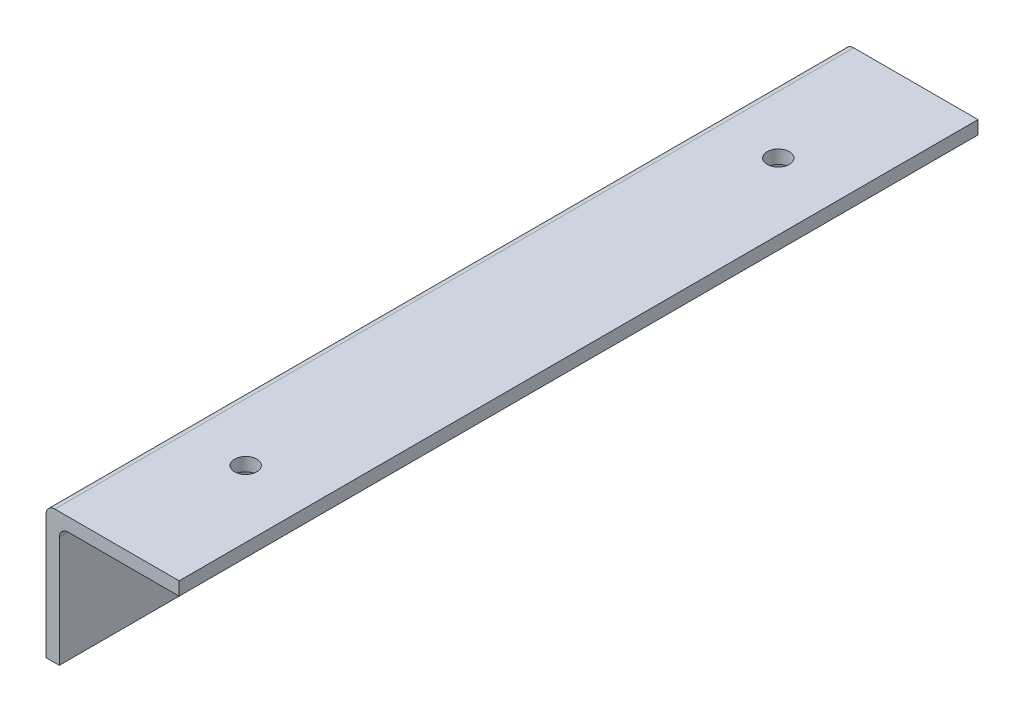
SolidWorks part; units mm, degrees
ref_plane "Plan de face" through (0, 0, 0) normal (0, 0, 1) x (1, 0, 0)
ref_plane "Plan de dessus" through (0, 0, 0) normal (0, 1, 0) x (1, 0, 0)
ref_plane "Plan de droite" through (0, 0, 0) normal (1, 0, 0) x (0, 0, -1)
sketch "Esquisse1" plane through (0, 0, 0) normal (0, 0, 1) x (1, 0, 0)
  line L0 (0, 0) -> (0, -30)
  line L1 (0, -30) -> (3, -30)
  line L2 (3, -30) -> (3, -3)
  line L3 (3, -3) -> (30, -3)
  line L4 (30, -3) -> (30, 0)
  line L5 (30, 0) -> (0, 0)
  dimension "D1" = 30
  dimension "D2" = 30
  dimension "D3" = 3
  dimension "D4" = 3
extrude "Boss.-Extru.1" add sketch "Esquisse1" along normal blind 180
sketch "Esquisse2" plane through (3, 0, 0) normal (1, 0, 0) x (0, 0, -1)
  line L0 (-180, -30) -> (0, -30) construction
  line L1 (-180, -30) -> (-180, -3) construction
  line L2 (0, -30) -> (0, -3) construction
  circle A0 centre (-30, -15) radius 3
  circle A1 centre (-150, -15) radius 3
  dimension "D1" = 6
  dimension "D2" = 6
  dimension "D3" = 15
  dimension "D4" = 15
  dimension "D5" = 30
  dimension "D6" = 30
  dimension "D7" = 120
extrude "Enlèv. mat.-Extru.1" cut sketch "Esquisse2" against normal blind 180
sketch "Esquisse3" plane through (0, -3, 0) normal (0, -1, 0) x (1, 0, 0)
  line L0 (3, 0) -> (30, 0) construction
  line L1 (3, 180) -> (30, 180) construction
  line L2 (30, 180) -> (0, 180) construction
  line L3 (0, 180) -> (0, 0) construction
  circle A0 centre (15, 150) radius 2.5
  circle A1 centre (15, 30) radius 2.5
  dimension "D1" = 5
  dimension "D2" = 5
  dimension "D3" = 30
  dimension "D4" = 30
  dimension "D5" = 120
  dimension "D6" = 180
  dimension "D7" = 15
  dimension "D8" = 15
extrude "Enlèv. mat.-Extru.2" cut sketch "Esquisse3" against normal blind 180
fillet "Congé1" radius 2 2 edges at (0, 0, 90) (3, -3, 90)
